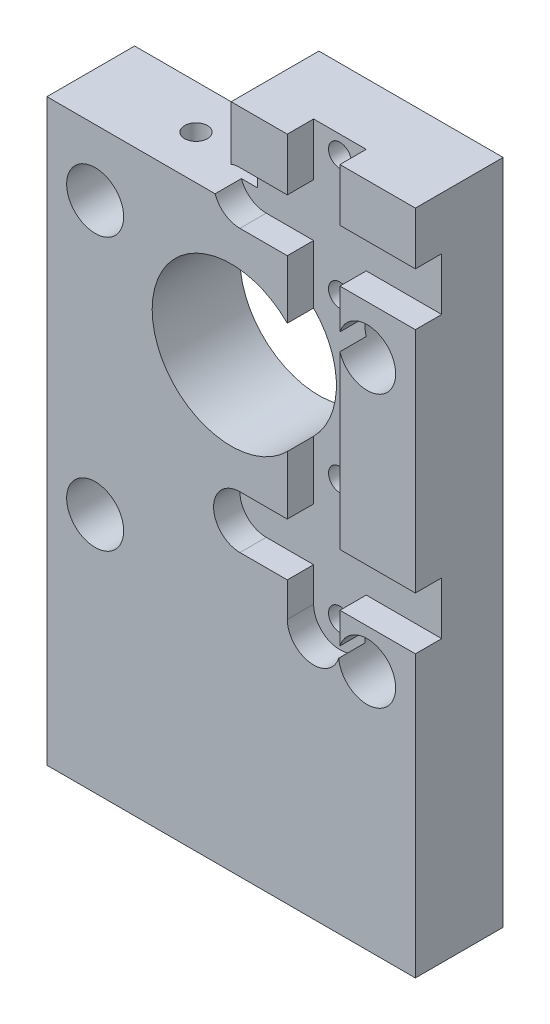
SolidWorks part; units mm, degrees
ref_plane "Front Plane" through (0, 0, 0) normal (0, 0, 1) x (1, 0, 0)
ref_plane "Top Plane" through (0, 0, 0) normal (0, 1, 0) x (1, 0, 0)
ref_plane "Right Plane" through (0, 0, 0) normal (1, 0, 0) x (0, 0, -1)
sketch "Sketch1" plane through (0, 0, 0) normal (0, 0, 1) x (1, 0, 0)
  line L1 (0, 0) -> (42, 0)
  line L2 (0, 0) -> (0, 66)
  line L3 (42, 76) -> (42, 66)
  line L4 (42, 0) -> (42, 66)
  line L8 (0, 66) -> (21, 66)
  line L9 (21, 66) -> (21, 76)
  line L10 (42, 76) -> (21, 76)
extrude "Boss-Extrude1" add sketch "Sketch1" along normal blind 10
sketch "Sketch2" plane through (0, 0, 10) normal (0, 0, 1) x (1, 0, 0)
  circle A0 centre (21, 51) radius 9
extrude "Cut-Extrude1" cut sketch "Sketch2" against normal up to next
sketch "Sketch3" plane through (0, 0, 10) normal (0, 0, 1) x (1, 0, 0)
  line L6 (27.4, 32) -> (27.4, 28.1)
  line L12 (27.4, 76) -> (33.4, 76)
  line L19 (27.4, 76) -> (27.4, 70)
  line L22 (33.4, 76) -> (33.4, 70)
  line L23 (33.4, 32) -> (42, 32)
  line L27 (22, 64) -> (27.4, 64)
  line L29 (22, 70) -> (27.4, 70)
  line L30 (42, 64) -> (42, 70)
  line L33 (22, 32) -> (27.4, 32)
  line L35 (22, 38) -> (27.4, 38)
  line L36 (42, 32) -> (42, 38)
  line L39 (33.4, 32) -> (33.4, 28.1)
  line L40 (33.4, 38) -> (42, 38)
  line L41 (27.4, 64) -> (27.4, 38)
  line L42 (33.4, 64) -> (33.4, 38)
  line L43 (33.4, 64) -> (42, 64)
  line L44 (33.4, 70) -> (42, 70)
  arc A0 (27.4, 28.1) -> (33.4, 28.1) centre (30.4, 28.1) ccw
  arc A1 (22, 38) -> (22, 32) centre (22, 35) ccw
  arc A2 (22, 70) -> (22, 64) centre (22, 67) ccw
  point P5 (30.6126, 48.8306)
  point P9 (32.1603, 66.561)
  point P14 (33.4194, 33.7)
extrude "Cut-Extrude2" cut sketch "Sketch3" against normal blind 3
sketch "Sketch4" plane through (0, 0, 10) normal (0, 0, 1) x (1, 0, 0)
  point P0 (5.5, 58.5)
  point P2 (36.5, 58.5)
  point P4 (5.5, 27.5)
  point P6 (36.5, 27.5)
hole_wizard "CBORE for M3 Pan Head Screw1" positions "Sketch4" profile "Sketch5" counterbore size "M3" standard "JIS" end condition through all
sketch "Sketch5" plane through (5.5, 58.5, 10) normal (1, 0, 0) x (0, -1, 0)
  line L0 (0, 0) -> (0, 10)
  line L1 (0, 10) -> (1.7, 10)
  line L3 (1.7, 10) -> (1.7, 6.5)
  line L4 (1.7, 6.5) -> (3.25, 6.5)
  line L5 (3.25, 6.5) -> (3.25, 0)
  line L7 (3.25, 0) -> (0, 0)
  line L11 (0, -6.35) -> (0, 107.95) construction
  dimension "Thru Hole Dia." = 3.4
  dimension "Thru Hole Depth" = 10
  dimension "C'Bore Dia." = 6.5
  dimension "C'Bore Depth" = 6.5
sketch "Sketch6" plane through (0, 0, 7) normal (0, 0, 1) x (1, 0, 0)
  point P0 (30.4, 73.9)
  point P2 (30.4, 60.1)
  point P4 (30.4, 41.9)
  point P6 (30.4, 28.1)
hole_wizard "M3x0.5 Tapped Hole1" positions "Sketch6" profile "Sketch7" tap size "M3x0.5" standard "JIS" end condition through all
sketch "Sketch7" plane through (30.4, 73.9, 7) normal (1, 0, 0) x (0, -1, 0)
  line L0 (0, 0) -> (0, 7)
  line L1 (0, 7) -> (1.3, 7)
  line L2 (1.3, 7) -> (1.3, 0)
  line L5 (1.3, 0) -> (0, 0)
  line L11 (0, -6.35) -> (0, 107.95) construction
  dimension "Thru Tap Drill Dia." = 2.6
  dimension "Thru Tap Drill Depth" = 7
cosmetic thread "Hole Thread4" parameters "D1"=5, "D2"=3
cosmetic thread "Hole Thread5" parameters "D1"=5, "D2"=3
cosmetic thread "Hole Thread6" parameters "D1"=5, "D2"=3
cosmetic thread "Hole Thread7" parameters "D1"=5, "D2"=3
sketch "Sketch8" plane through (0, 0, 0) normal (0, -1, 0) x (-1, 0, 0)
  point P0 (-10, -5)
  point P2 (-32, -5)
  point P5 (0, 0)
  point P6 (0, 0)
hole_wizard "M3x0.5 Tapped Hole2" positions "Sketch8" profile "Sketch9" tap size "M3x0.5" standard "JIS"
sketch "Sketch9" plane through (10, 0, 5) normal (1, 0, 0) x (0, 0, -1)
  line L0 (0, 0) -> (0, 9.7811)
  line L1 (0, 9.7811) -> (1.3, 9)
  line L2 (1.3, 9) -> (1.3, 0)
  line L5 (1.3, 0) -> (0, 0)
  line L10 (0, 9.7811) -> (-1.3, 9) construction
  line L11 (0, -6.35) -> (0, 107.95) construction
  dimension "Tap Drill Dia." = 2.6
  dimension "Tap Drill Depth" = 9
  dimension "Drill Angle" = 118
cosmetic thread "Hole Thread8" parameters "D1"=6, "D2"=3
cosmetic thread "Hole Thread9" parameters "D1"=6, "D2"=3
sketch "Sketch10" plane through (0, 66, 0) normal (0, 1, 0) x (1, 0, 0)
  point P0 (12, -5)
  point P3 (0, 0)
  point P4 (0, 0)
hole_wizard "M3x0.5 Tapped Hole3" positions "Sketch10" profile "Sketch11" tap size "M3x0.5" standard "JIS"
sketch "Sketch11" plane through (12, 66, 5) normal (1, 0, 0) x (0, 0, 1)
  line L0 (0, 0) -> (0, 9.7811)
  line L1 (0, 9.7811) -> (1.3, 9)
  line L2 (1.3, 9) -> (1.3, 0)
  line L5 (1.3, 0) -> (0, 0)
  line L10 (0, 9.7811) -> (-1.3, 9) construction
  line L11 (0, -6.35) -> (0, 107.95) construction
  dimension "Tap Drill Dia." = 2.6
  dimension "Tap Drill Depth" = 9
  dimension "Drill Angle" = 118
cosmetic thread "Hole Thread10" parameters "D1"=6, "D2"=3
